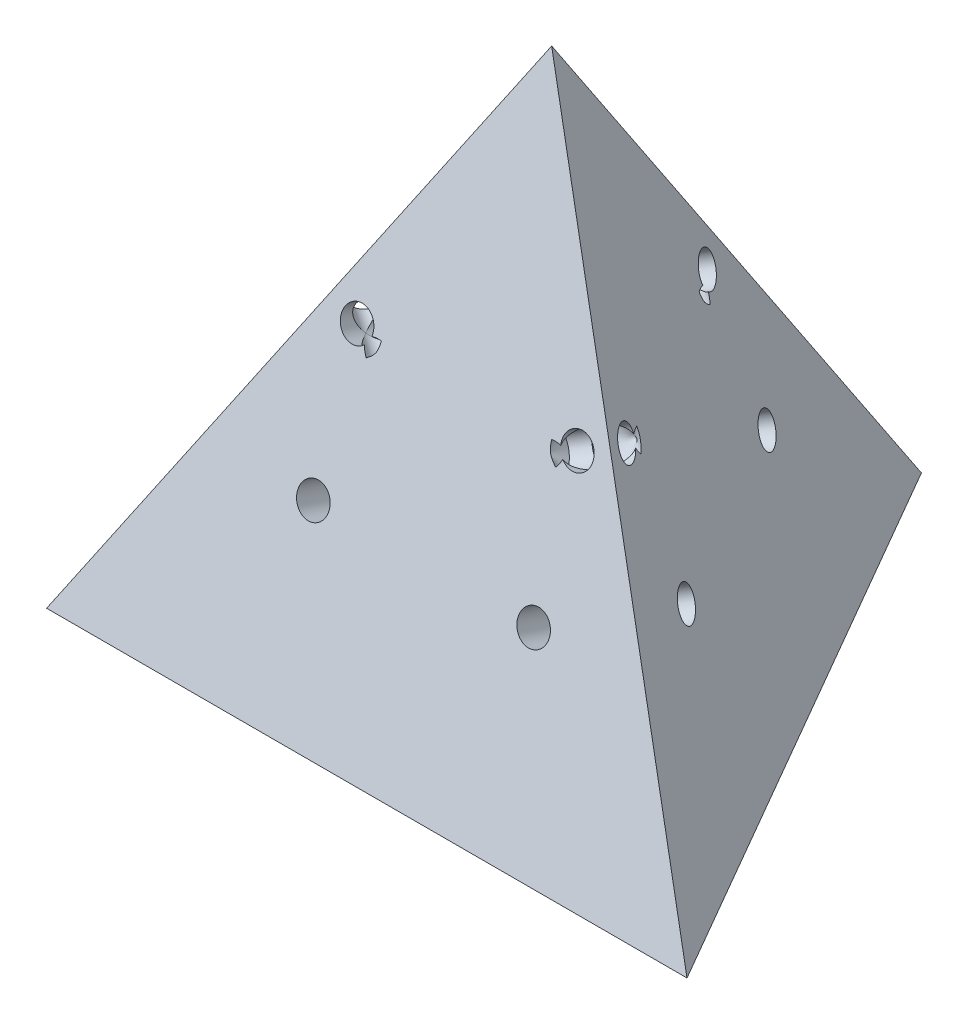
SolidWorks part; units mm, degrees
ref_plane "前基準面" through (0, 0, 0) normal (0, 0, 1) x (1, 0, 0)
ref_plane "上基準面" through (0, 0, 0) normal (0, 1, 0) x (1, 0, 0)
ref_plane "右基準面" through (0, 0, 0) normal (1, 0, 0) x (0, 0, -1)
sketch "草圖1" plane through (0, 0, 0) normal (0, 1, 0) x (1, 0, 0)
  line L0 (0, -1000) -> (0, 49000) construction
  line L1 (0, 0) -> (-125, 0)
  line L2 (-125, 0) -> (0, 216.5064)
  line L3 (0, 216.5064) -> (125, 0)
  line L4 (125, 0) -> (0, 0)
  dimension "D1" = 250
  dimension "D2" = 250
ref_plane "平面1" through (0, 216.5, 0) normal (0, 1, 0) x (-1, 0, 0)
sketch "草圖2" plane through (0, 216.5, 0) normal (0, 1, 0) x (-1, 0, 0)
  line L0 (-125, 0) -> (62.5, -108.2532) construction
  line L1 (125, 0) -> (0, -216.5064) construction
  line L2 (125, 0) -> (-62.5, -108.2532) construction
  line L3 (0, -216.5064) -> (-125, 0) construction
  point P0 (0, -72.1688)
loft "疊層拉伸1" add profiles "草圖1", "草圖2"
hole_wizard "M14x1.5 螺紋孔1" positions "草圖4" profile "草圖3" tap size "M14x1.5" standard "ISO"
sketch "草圖4" plane through (0, 0, 0) normal (0, 0.3162, 0.9487) x (1, 0, 0)
  line L0 (0, 228.2117) -> (0, 0) construction
  line L2 (-125, 0) -> (0, 0) construction
  point P0 (-43, 124)
  point P1 (43, 124)
  point P3 (43, 70)
  point P5 (-43, 70)
  dimension "D1" = 86
  dimension "D2" = 54
  dimension "D3" = 70
sketch "草圖3" plane through (-43, 117.6364, -39.2133) normal (1, 0, 0) x (0, -0.9487, 0.3162)
  line L0 (0, 0) -> (0, 23.7554)
  line L1 (0, 23.7554) -> (6.25, 20)
  line L2 (6.25, 20) -> (6.25, 0)
  line L5 (6.25, 0) -> (0, 0)
  line L10 (0, 23.7554) -> (-6.25, 20) construction
  line L11 (0, -6.35) -> (0, 107.95) construction
  dimension "螺孔鑽直徑" = 12.5
  dimension "螺孔鑽深度" = 20
  dimension "導頭角度" = 118
cosmetic thread "鑽孔螺紋1" parameters "D1"=20, "D2"=14
cosmetic thread "鑽孔螺紋2" parameters "D1"=20, "D2"=14
cosmetic thread "鑽孔螺紋3" parameters "D1"=20, "D2"=14
cosmetic thread "鑽孔螺紋4" parameters "D1"=20, "D2"=14
ref_axis "基準軸1" through (0, 216.5, -72.1688) along (0, -1, 0)
pattern_circular "環狀複製排列1" count 3 over 360 about axis through (0, 216.5, -72.1688) along (0, -1, 0) of "M14x1.5 螺紋孔1"
